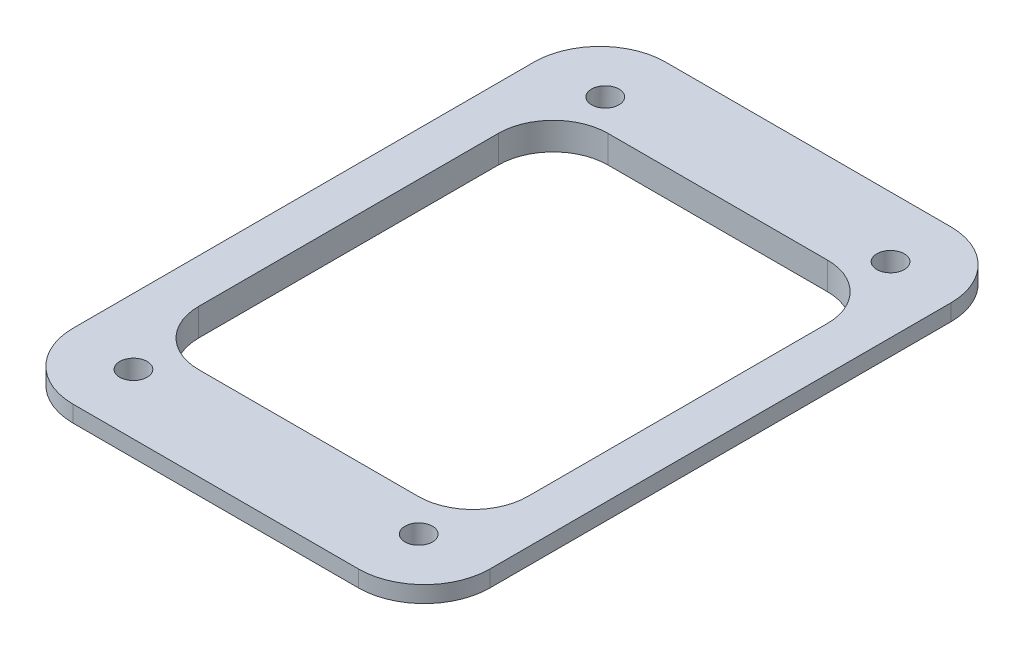
SolidWorks part; units mm, degrees
ref_plane "Piano frontale" through (0, 0, 0) normal (0, 0, 1) x (1, 0, 0)
ref_plane "Piano superiore" through (0, 0, 0) normal (0, 1, 0) x (1, 0, 0)
ref_plane "Piano destro" through (0, 0, 0) normal (1, 0, 0) x (0, 0, -1)
sketch "Schizzo2" plane through (0, 0, 0) normal (0, 1, 0) x (1, 0, 0)
  line L1 (-3, 0) -> (-31, 0)
  line L2 (0, 3) -> (0, 47)
  line L3 (-3, 50) -> (-31, 50)
  line L4 (-34, 3) -> (-34, 47)
  line L5 (-27, 43.75) -> (-7, 43.75)
  line L6 (-32, 38.75) -> (-32, 11.45)
  line L7 (-27, 6.45) -> (-7, 6.45)
  line L8 (-2, 38.75) -> (-2, 11.45)
  arc A0 (-31, 0) -> (-34, 3) centre (-31, 3) cw
  arc A1 (0, 3) -> (-3, 0) centre (-3, 3) cw
  arc A2 (0, 47) -> (-3, 50) centre (-3, 47) ccw
  arc A3 (-31, 50) -> (-34, 47) centre (-31, 47) ccw
  arc A4 (-27, 6.45) -> (-32, 11.45) centre (-27, 11.45) cw
  arc A5 (-7, 6.45) -> (-2, 11.45) centre (-7, 11.45) ccw
  arc A6 (-2, 38.75) -> (-7, 43.75) centre (-7, 38.75) ccw
  arc A7 (-27, 43.75) -> (-32, 38.75) centre (-27, 38.75) ccw
  point P7 (-34, 0)
  point P10 (0, 0)
  point P13 (0, 50)
  point P16 (-34, 50)
  point P23 (-32, 6.45)
  point P28 (-2, 43.75)
  point P31 (-32, 43.75)
  dimension "D3" = 3
  dimension "D6" = 5
  dimension "D1" = 34
  dimension "D2" = 50
  dimension "D4" = 30
  dimension "D5" = 37.3
  dimension "D7" = 6.25
  dimension "D8" = 2
extrude "Estrusione-Estrusione1" add sketch "Schizzo2" along normal blind 1
sketch "Schizzo3" plane through (0, 1, 0) normal (0, 1, 0) x (1, 0, 0)
  line L0 (-3, 50) -> (-31, 50) construction
  line L1 (-30, 52) -> (-4, 52)
  line L2 (-36, 46) -> (-36, 4)
  line L3 (-30, -2) -> (-4, -2)
  line L4 (2, 46) -> (2, 4)
  line L5 (0, 3) -> (0, 47) construction
  line L6 (-31, 0) -> (-3, 0) construction
  line L7 (-34, 47) -> (-34, 3) construction
  line L8 (-27, 6.45) -> (-7, 6.45)
  line L9 (-2, 11.45) -> (-2, 38.75)
  line L10 (-7, 43.75) -> (-27, 43.75)
  line L11 (-32, 38.75) -> (-32, 11.45)
  arc A0 (-30, -2) -> (-36, 4) centre (-30, 4) cw
  arc A1 (2, 4) -> (-4, -2) centre (-4, 4) cw
  arc A2 (2, 46) -> (-4, 52) centre (-4, 46) ccw
  arc A3 (-36, 46) -> (-30, 52) centre (-30, 46) cw
  arc A4 (-27, 6.45) -> (-32, 11.45) centre (-27, 11.45) cw
  arc A5 (-2, 11.45) -> (-7, 6.45) centre (-7, 11.45) cw
  arc A6 (-2, 38.75) -> (-7, 43.75) centre (-7, 38.75) ccw
  arc A7 (-27, 43.75) -> (-32, 38.75) centre (-27, 38.75) ccw
  dimension "D5" = 6
  dimension "D6" = 5
  dimension "D1" = 2
  dimension "D2" = 2
  dimension "D3" = 2
  dimension "D4" = 2
  dimension "D7" = 37.3
  dimension "D8" = 4
  dimension "D9" = 30
extrude "Estrusione-Estrusione2" add sketch "Schizzo3" along normal blind 1.5
sketch "Schizzo4" plane through (0, 0, 0) normal (0, -1, 0) x (1, 0, 0)
  line L0 (-3, -50) -> (-31, -50) construction
  line L1 (-27.165, -45.83) -> (-6.825, -45.83)
  line L2 (-27.165, -45.83) -> (-27.165, -48.37)
  line L3 (-27.165, -48.37) -> (-6.825, -48.37)
  line L4 (-6.825, -45.83) -> (-6.825, -48.37)
  line L5 (-34, -47) -> (-34, -3) construction
  dimension "D1" = 1.63
  dimension "D2" = 6.835
  dimension "D3" = 20.34
  dimension "D4" = 2.54
extrude "Taglio-Estrusione1" cut sketch "Schizzo4" against normal blind 1.5
sketch "Schizzo5" plane through (0, 2.5, 0) normal (0, 1, 0) x (1, 0, 0)
  line L0 (-36, 46) -> (-36, 4) construction
  line L1 (-4, 52) -> (-30, 52) construction
  line L2 (-30, 46.5) -> (-4, 46.5) construction
  line L3 (-4, 46.5) -> (-4, 3.5) construction
  line L4 (-4, 3.5) -> (-30, 3.5) construction
  line L5 (-30, 3.5) -> (-30, 46.5) construction
  line L6 (-30, -2) -> (-4, -2) construction
  circle A0 centre (-30, 46.5) radius 1.25
  circle A1 centre (-4, 46.5) radius 1.25
  circle A2 centre (-4, 3.5) radius 1.25
  circle A3 centre (-30, 3.5) radius 1.25
  dimension "D5" = 2.5
  dimension "D1" = 6
  dimension "D2" = 5.5
  dimension "D3" = 26
  dimension "D4" = 5.5
extrude "Taglio-Estrusione2" cut sketch "Schizzo5" against normal blind 10
